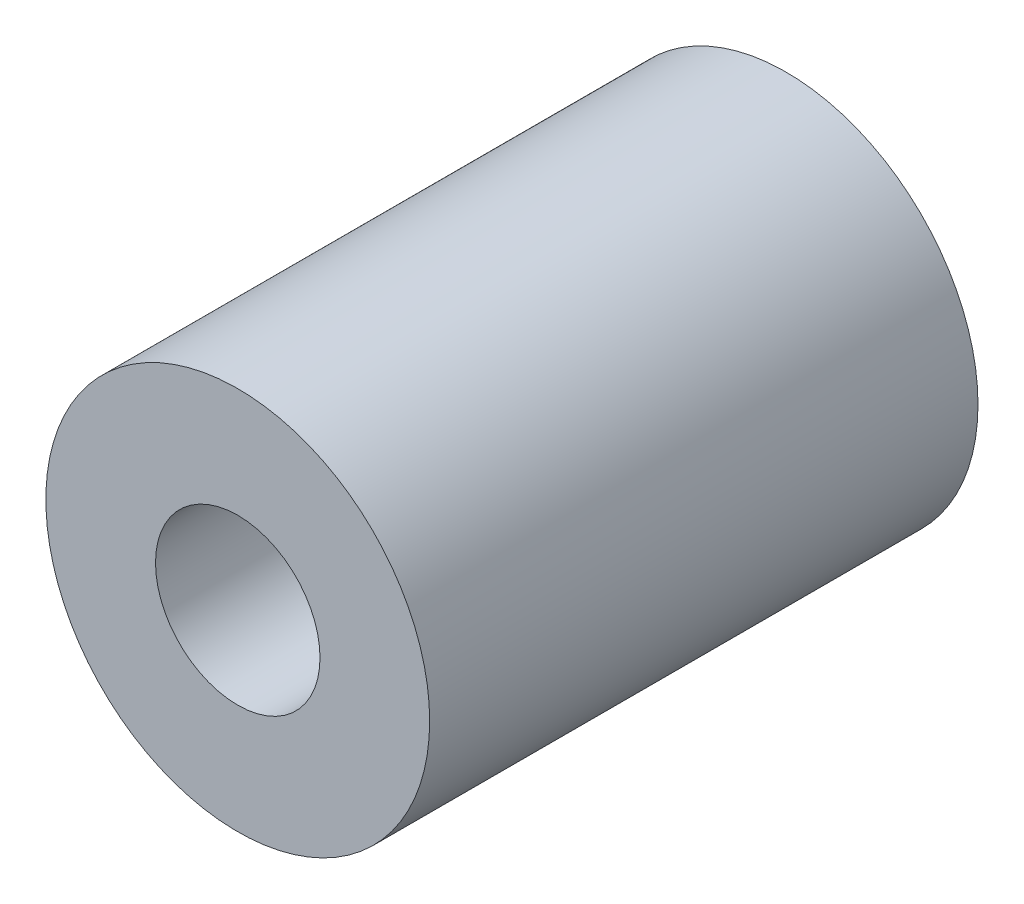
SolidWorks part; units mm, degrees
material "Alliage 1060"
ref_plane "Plan de face" through (0, 0, 0) normal (0, 0, 1) x (1, 0, 0)
ref_plane "Plan de dessus" through (0, 0, 0) normal (0, 1, 0) x (1, 0, 0)
ref_plane "Plan de droite" through (0, 0, 0) normal (1, 0, 0) x (0, 0, -1)
sketch "Esquisse1" plane through (0, 0, 0) normal (0, 0, 1) x (1, 0, 0)
  circle A0 centre (0, 0) radius 1.5
  circle A1 centre (0, 0) radius 3.5
  dimension "D1" = 3
  dimension "D2" = 7
extrude "Boss.-Extru.1" add sketch "Esquisse1" along normal blind 10
